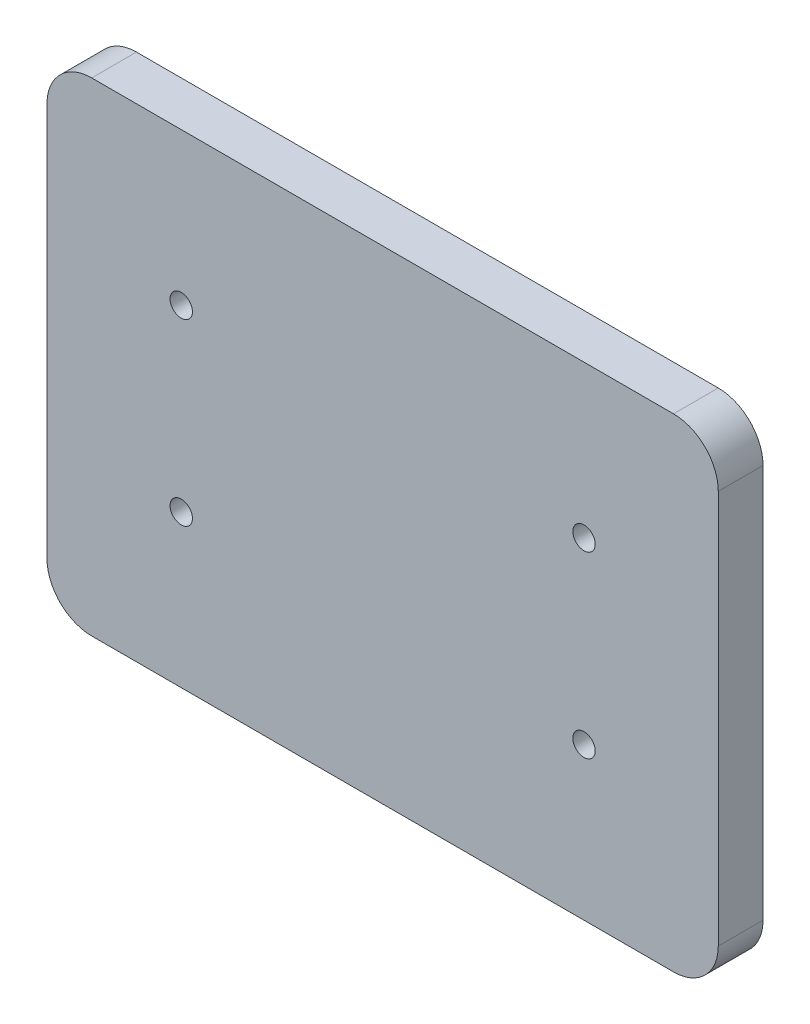
SolidWorks part; units mm, degrees
material "5052-H32"
ref_plane "Plan de face" through (0, 0, 0) normal (0, 0, 1) x (1, 0, 0)
ref_plane "Plan de dessus" through (0, 0, 0) normal (0, 1, 0) x (1, 0, 0)
ref_plane "Plan de droite" through (0, 0, 0) normal (1, 0, 0) x (0, 0, -1)
sketch "Sketch1" plane through (0, 0, 0) normal (0, 0, 1) x (1, 0, 0)
  line L1 (-75, -54) -> (75, -54)
  line L2 (-75, -54) -> (-75, 54)
  line L3 (-75, 54) -> (75, 54)
  line L4 (75, -54) -> (75, 54)
  line L5 (-75, -54) -> (75, 54) construction
  line L6 (-75, 54) -> (75, -54) construction
  point P0 (0, 0)
  dimension "D1" = 108
  dimension "D2" = 150
extrude "Boss-Extrude1" add sketch "Sketch1" along normal blind 10
sketch "Sketch2" plane through (0, 0, 10) normal (0, 0, 1) x (1, 0, 0)
  line L0 (-45, 54) -> (-45, -54)
  line L1 (75, 54) -> (-75, 54) construction
  line L2 (-75, -54) -> (75, -54) construction
  dimension "D1" = 45
hole_wizard "M6 Tapped Hole1" positions "Sketch3" profile "Sketch4" tap size "M6" standard "ISO"
sketch "Sketch3" plane through (0, 0, 10) normal (0, 0, 1) x (1, 0, 0)
  point P0 (-44.9979, 20)
  point P2 (-44.9979, -20)
  dimension "D1" = 40
  dimension "D2" = 20
sketch "Sketch4" plane through (-44.9979, 20, 10) normal (1, 0, 0) x (0, -1, 0)
  line L0 (0, 0) -> (0, 16.5022)
  line L1 (0, 16.5022) -> (2.5, 15)
  line L2 (2.5, 15) -> (2.5, 0)
  line L5 (2.5, 0) -> (0, 0)
  line L10 (0, 16.5022) -> (-2.5, 15) construction
  line L11 (0, -6.35) -> (0, 107.95) construction
  dimension "Tap Drill Dia." = 5
  dimension "Tap Drill Depth" = 15
  dimension "Drill Angle" = 118
cosmetic thread "Hole Thread1"
cosmetic thread "Hole Thread2"
mirror "Mirror1" about plane through (0, 0, 0) normal (1, 0, 0) of "M6 Tapped Hole1"
cosmetic thread "Hole Thread3"
cosmetic thread "Hole Thread4"
fillet "Fillet1" radius 10 4 edges at (75, 54, 5) (75, -54, 5) (-75, 54, 5) (-75, -54, 5)
